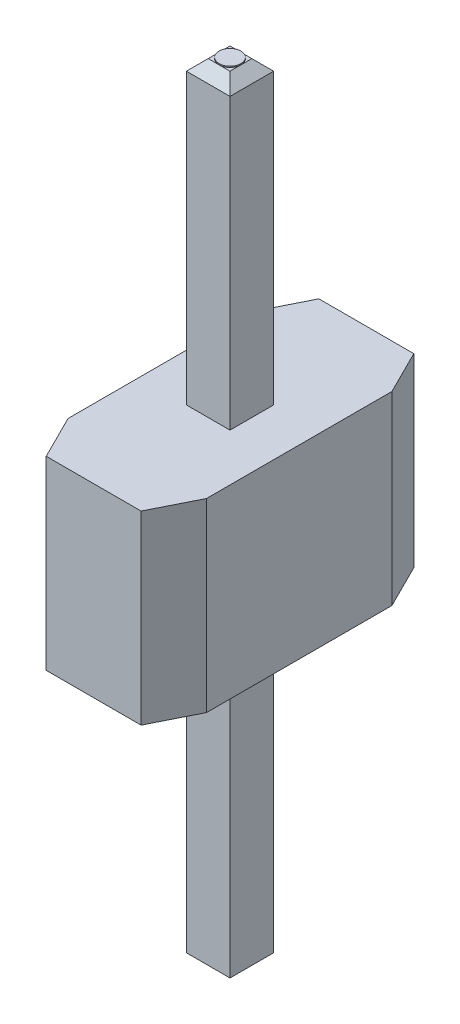
SolidWorks part; units mm, degrees
ref_plane "前视基准面" through (0, 0, 0) normal (0, 0, 1) x (1, 0, 0)
ref_plane "上视基准面" through (0, 0, 0) normal (0, 1, 0) x (1, 0, 0)
ref_plane "右视基准面" through (0, 0, 0) normal (1, 0, 0) x (0, 0, -1)
sketch "草图1" plane through (0, 0, 0) normal (0, 1, 0) x (1, 0, 0)
  line L4 (8.0596, 1.1443) -> (8.0596, 2.8443)
  line L5 (8.2596, 3.2443) -> (9.1296, 3.2443)
  line L6 (9.3296, 2.8443) -> (9.3296, 1.1443)
  line L7 (9.1296, 0.7443) -> (8.2596, 0.7443)
  line L10 (8.2596, 3.2443) -> (8.0596, 2.8443)
  line L12 (9.1296, 3.2443) -> (9.3296, 2.8443)
  line L14 (8.0596, 1.1443) -> (8.2596, 0.7443)
  line L15 (9.1296, 0.7443) -> (9.3296, 1.1443)
extrude "凸台-拉伸1" add sketch "草图1" along normal blind 1.7
sketch "草图2" plane through (0, 1.7, 0) normal (0, 1, 0) x (1, 0, 0)
  line L4 (8.6946, 2.1943) -> (8.4946, 2.1943)
  line L5 (8.4946, 2.1943) -> (8.4946, 1.7943)
  line L6 (8.4946, 1.7943) -> (8.8946, 1.7943)
  line L7 (8.8946, 1.7943) -> (8.8946, 2.1943)
  line L8 (8.8946, 2.1943) -> (8.6946, 2.1943)
extrude "凸台-拉伸2" add sketch "草图2" along normal blind 2.75 and the other way blind 4.45
chamfer "倒角1" distance 0.1 angle 45 4 edges at (8.6946, 4.45, -2.1943) (8.8946, 4.45, -1.9943) (8.6946, 4.45, -1.7943) (8.4946, 4.45, -1.9943)
chamfer "倒角2" distance 0.1 angle 45 4 edges at (8.8946, -2.75, -1.9943) (8.6946, -2.75, -1.7943) (8.4946, -2.75, -1.9943) (8.6946, -2.75, -2.1943)
sketch "草图3" plane through (0, 4.45, 0) normal (0, 1, 0) x (1, 0, 0)
  circle A0 centre (8.6946, 1.9943) radius 0.1
extrude "凸台-拉伸3" add sketch "草图3" along normal blind 0.01
